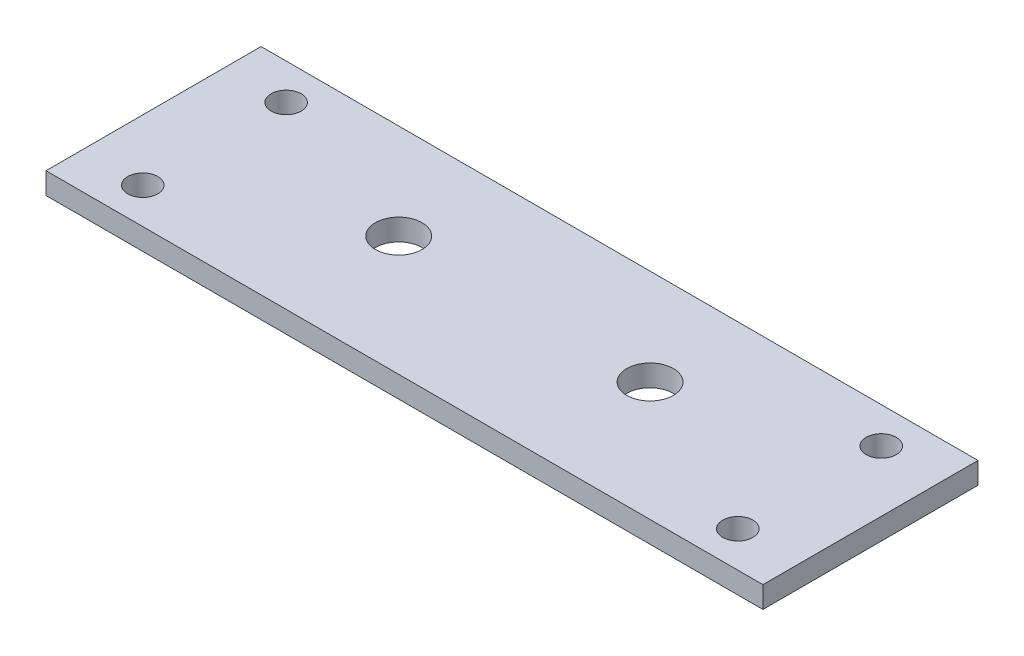
SolidWorks part; units mm, degrees
ref_plane "Front Plane" through (0, 0, 0) normal (0, 0, 1) x (1, 0, 0)
ref_plane "Top Plane" through (0, 0, 0) normal (0, 1, 0) x (1, 0, 0)
ref_plane "Right Plane" through (0, 0, 0) normal (1, 0, 0) x (0, 0, -1)
sketch "Sketch1" plane through (0, 0, 0) normal (0, 1, 0) x (1, 0, 0)
  line L0 (92.7948, -1.6097) -> (45.9989, -1.6097) construction
  line L1 (-40.7907, 13.3903) -> (59.2093, 13.3903)
  line L2 (-40.7907, 13.3903) -> (-40.7907, -16.6097)
  line L3 (-40.7907, -16.6097) -> (59.2093, -16.6097)
  line L4 (59.2093, 13.3903) -> (59.2093, -16.6097)
  line L5 (9.2093, 24.2126) -> (9.2093, -31.2739) construction
  circle A0 centre (50.7093, 8.3903) radius 2.1
  circle A1 centre (50.7093, -11.6097) radius 2.1
  circle A2 centre (-32.2907, 8.3903) radius 2.1
  circle A3 centre (-32.2907, -11.6097) radius 2.1
  circle A4 centre (-8.2907, 0.0903) radius 3.25
  circle A5 centre (26.8596, 0) radius 3.25
  dimension "D3" = 4.2
  dimension "D4" = 5
  dimension "D5" = 41.5
  dimension "D8" = 6.5
  dimension "D1" = 100
  dimension "D2" = 30
  dimension "D6" = 15
  dimension "D7" = 50
extrude "Boss-Extrude1" add sketch "Sketch1" along normal blind 3
